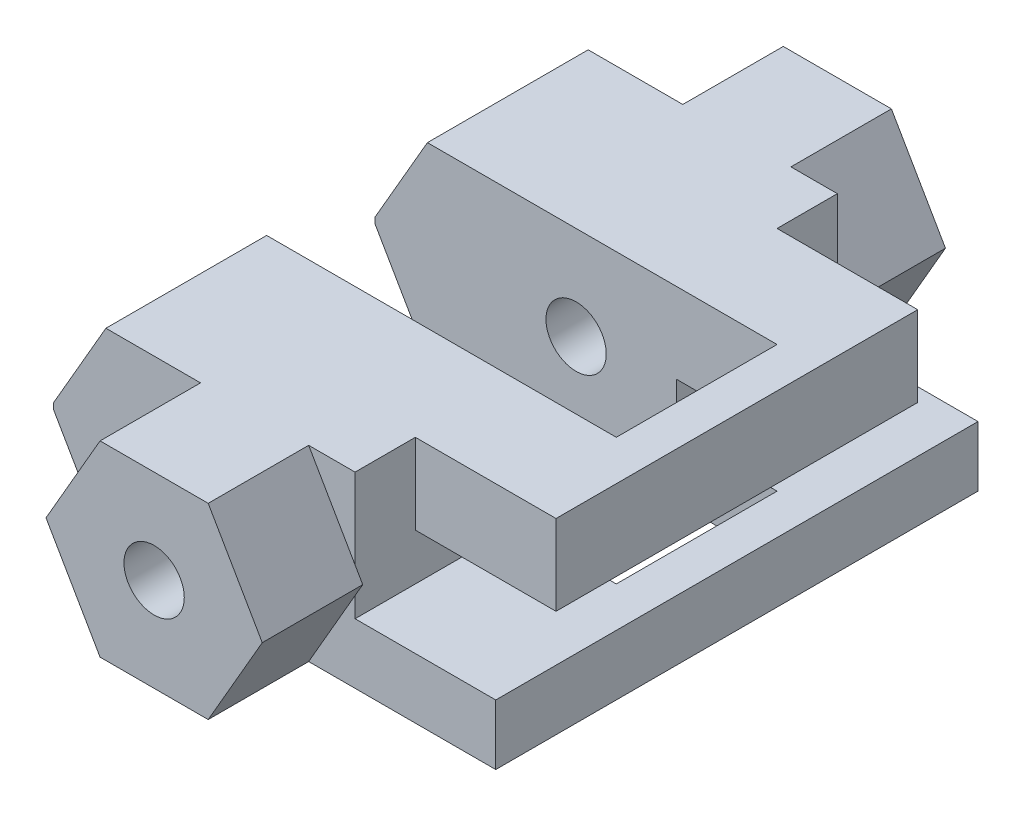
SolidWorks part; units mm, degrees
ref_plane "Plan de face" through (0, 0, 0) normal (0, 0, 1) x (1, 0, 0)
ref_plane "Plan de dessus" through (0, 0, 0) normal (0, 1, 0) x (1, 0, 0)
ref_plane "Plan de droite" through (0, 0, 0) normal (1, 0, 0) x (0, 0, -1)
sketch "Esquisse1" plane through (0, 0, 0) normal (0, 0, 1) x (1, 0, 0)
  line L1 (2.6906, 4.6603) -> (-2.6906, 4.6603)
  line L2 (-2.6906, 4.6603) -> (-5.3812, 0)
  line L3 (-5.3812, 0) -> (-2.6906, -4.6603)
  line L4 (-2.6906, -4.6603) -> (2.6906, -4.6603)
  line L5 (2.6906, -4.6603) -> (5.3812, 0)
  line L6 (5.3812, 0) -> (2.6906, 4.6603)
  line L7 (-5, 8.6603) -> (-10, 0) construction
  line L8 (-10, 0) -> (-5, -8.6603) construction
  line L9 (-5, -8.6603) -> (5, -8.6603) construction
  line L10 (5, -8.6603) -> (10, 0) construction
  line L11 (10, 0) -> (5, 8.6603) construction
  line L12 (5, 8.6603) -> (-5, 8.6603) construction
  circle A0 centre (0, 0) radius 4.6603 construction
  circle A1 centre (0, 0) radius 8.6603 construction
  circle A2 centre (0, 0) radius 1.5
  dimension "D3" = 3
  dimension "D1" = 10
  dimension "D2" = 4
extrude "Boss.-Extru.1" add sketch "Esquisse1" along normal blind 5
sketch "Esquisse3" plane through (0, 0, 0) normal (0, 0, -1) x (-1, 0, 0)
  line L1 (-12, 4.6603) -> (10, 4.6603)
  line L2 (-12, 4.6603) -> (-12, 0.6603)
  line L3 (-12, -4.6603) -> (10, -4.6603)
  line L4 (10, 4.6603) -> (10, -4.6603)
  line L6 (-12, -4.6603) -> (-12, -1.6603)
  line L7 (-12, -1.6603) -> (-5, -1.6603)
  line L8 (-5, -1.6603) -> (-5, 0.6603)
  line L9 (-5, 0.6603) -> (-12, 0.6603)
  circle A0 centre (0, 0) radius 1.5
  dimension "D1" = 10
  dimension "D2" = 12
  dimension "D3" = 7
  dimension "D4" = 3
  dimension "D5" = 4
extrude "Boss.-Extru.3" add sketch "Esquisse3" along normal blind 8
sketch "Esquisse4" plane through (0, 0, -8) normal (0, 0, -1) x (-1, 0, 0)
  line L0 (-12, -4.6603) -> (10, -4.6603) construction
  line L1 (-12, 4.6603) -> (-10, 4.6603)
  line L2 (-12, 4.6603) -> (-12, 0.6603)
  line L3 (-12, -4.6603) -> (-10, -4.6603)
  line L4 (-10, 4.6603) -> (-10, 0.6603)
  line L5 (0, 11.4648) -> (0, -11.93) construction
  line L10 (-10, 0.6603) -> (-12, 0.6603)
  line L11 (-12, -1.6603) -> (-10, -1.6603)
  line L12 (-12, -1.6603) -> (-12, -4.6603)
  line L13 (-10, -1.6603) -> (-10, -4.6603)
  dimension "D1" = 2
extrude "Boss.-Extru.4" add sketch "Esquisse4" along normal blind 4
sketch "Esquisse5" plane through (0, 4.6603, 0) normal (0, 1, 0) x (1, 0, 0)
  line L0 (2.6906, 0) -> (12, 0) construction
  line L1 (12, 0) -> (5, 0)
  line L2 (12, 0) -> (12, 3)
  line L3 (12, 3) -> (5, 3)
  line L4 (5, 0) -> (5, 3)
  line L5 (5, 8) -> (5, 0) construction
  dimension "D1" = 3
extrude "Enlèv. mat.-Extru.1" cut sketch "Esquisse5" against normal blind 4
mirror "Symétrie3" about plane through (0, 0, -12) normal (0, 0, 1) of "Enlèv. mat.-Extru.1", "Boss.-Extru.4", "Boss.-Extru.3", "Boss.-Extru.1"
chamfer "Chanfrein2" distance 4.5 distance2 2.6 2 edges at (-10, -4.6603, -20) (-10, 4.6603, -4)
chamfer "Chanfrein3" distance 2.6 distance2 4.5 2 edges at (-10, 4.6603, -20) (-10, -4.6603, -4)
